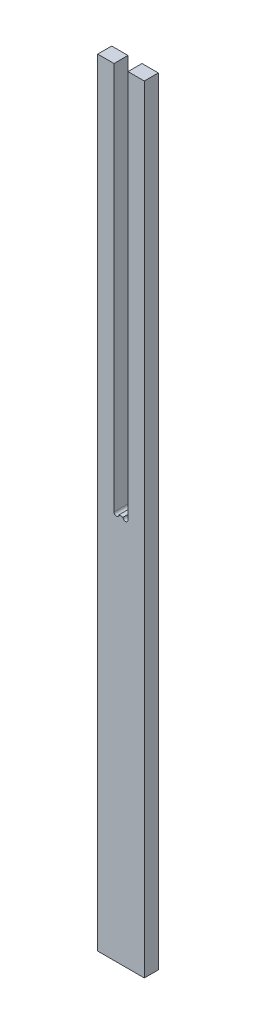
SolidWorks part; units mm, degrees
ref_plane "Piano frontale" through (0, 0, 0) normal (0, 0, 1) x (1, 0, 0)
ref_plane "Piano superiore" through (0, 0, 0) normal (0, 1, 0) x (1, 0, 0)
ref_plane "Piano destro" through (0, 0, 0) normal (1, 0, 0) x (0, 0, -1)
sketch "Schizzo1" plane through (0, 0, 0) normal (0, 0, 1) x (1, 0, 0)
  line L0 (-51.2222, 825) -> (-51.2222, 325)
  line L1 (-72.2222, 825) -> (-51.2222, 825)
  line L2 (-72.2222, 825) -> (-72.2222, -175)
  line L3 (-72.2222, -175) -> (-12.2222, -175)
  line L4 (-12.2222, 825) -> (-12.2222, -175)
  line L7 (-44.8722, 325) -> (-39.5722, 325)
  line L8 (-33.2222, 325) -> (-33.2222, 825)
  line L9 (-33.2222, 825) -> (-12.2222, 825)
  arc A0 (-33.2222, 325) -> (-39.5722, 325) centre (-36.3972, 325) cw
  arc A1 (-51.2222, 325) -> (-44.8722, 325) centre (-48.0472, 325) ccw
  point P0 (-42.766, 325)
  dimension "D5" = 3.175
  dimension "D6" = 3.175
  dimension "D1" = 60
  dimension "D2" = 1000
  dimension "D3" = 18
  dimension "D4" = 21
extrude "Estrusione-Estrusione1" add sketch "Schizzo1" along normal blind 18 contours L4 L3 L2 L1 L0 A1 L7 A0 L8 L9
